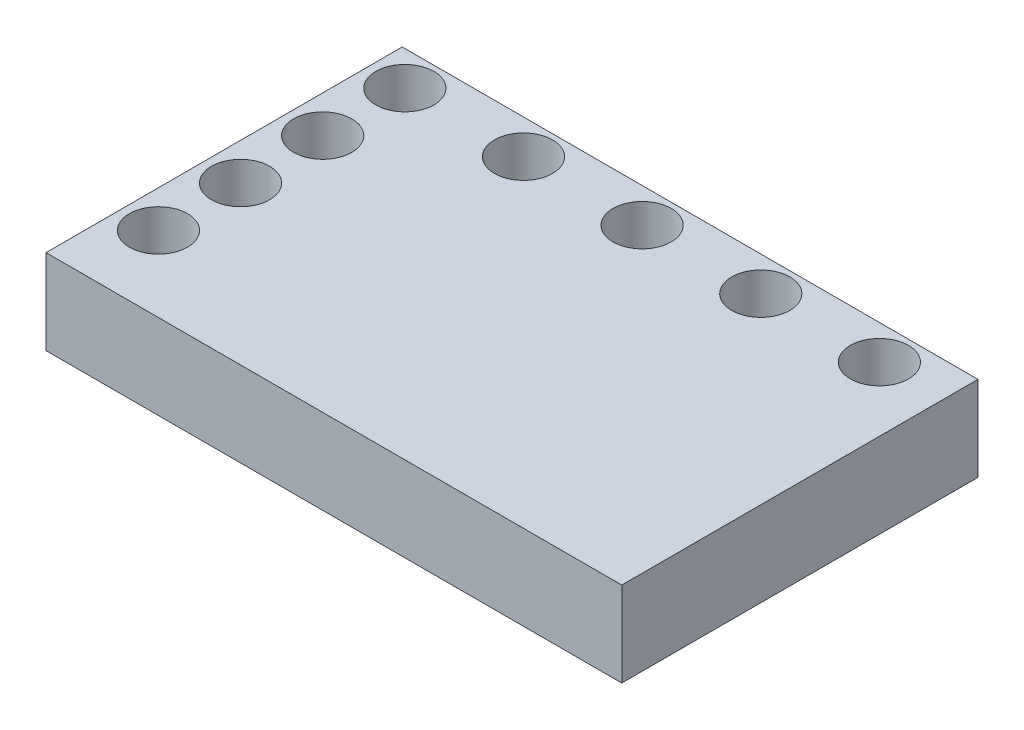
SolidWorks part; units mm, degrees
ref_plane "Front Plane" through (0, 0, 0) normal (0, 0, 1) x (1, 0, 0)
ref_plane "Top Plane" through (0, 0, 0) normal (0, 1, 0) x (1, 0, 0)
ref_plane "Right Plane" through (0, 0, 0) normal (1, 0, 0) x (0, 0, -1)
sketch "Sketch1" plane through (0, 0, 0) normal (0, 1, 0) x (1, 0, 0)
  line L1 (-146.0373, 46.0154) -> (174.4374, 46.0154)
  line L2 (-146.0373, 46.0154) -> (-146.0373, -152.2704)
  line L3 (-146.0373, -152.2704) -> (174.4374, -152.2704)
  line L4 (174.4374, 46.0154) -> (174.4374, -152.2704)
extrude "Boss-Extrude1" add sketch "Sketch1" along normal mid plane 47.244
sketch "Sketch2" plane through (0, 23.622, 0) normal (0, 1, 0) x (1, 0, 0)
  circle A0 centre (-125.4459, 26.8713) radius 16.1823
extrude "Cut-Extrude1" cut sketch "Sketch2" against normal blind 47.244
pattern_linear "LPattern1" count 5 spacing 66.04 along (1, 0, 0) count 4 spacing 45.72 along (0, 0, 1) of "Cut-Extrude1"
